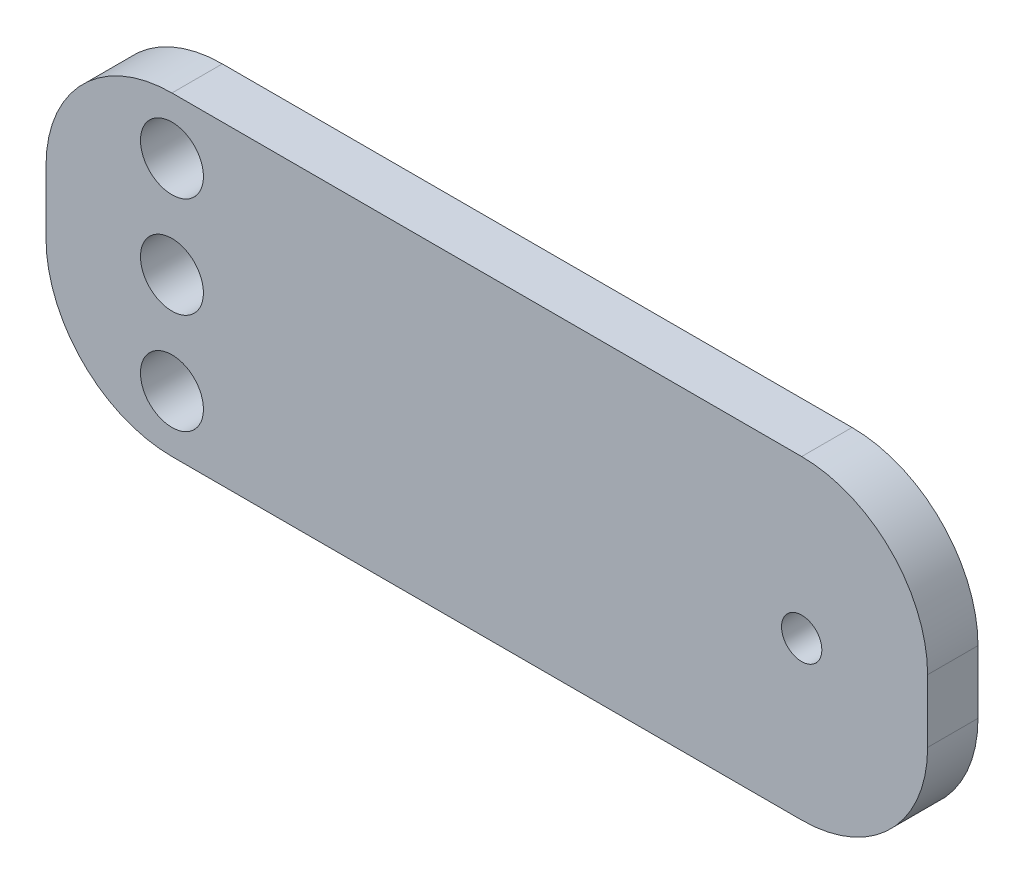
SolidWorks part; units mm, degrees
ref_plane "前视基准面" through (0, 0, 0) normal (0, 0, 1) x (1, 0, 0)
ref_plane "上视基准面" through (0, 0, 0) normal (0, 1, 0) x (1, 0, 0)
ref_plane "右视基准面" through (0, 0, 0) normal (1, 0, 0) x (0, 0, -1)
sketch "草图1" plane through (0, 0, 0) normal (0, 0, 1) x (1, 0, 0)
  line L0 (-35, 0) -> (35, 0) construction
  line L1 (-35, -12.5) -> (35, -12.5)
  line L2 (-35, -12.5) -> (-35, 12.5)
  line L3 (-35, 12.5) -> (35, 12.5)
  line L4 (35, -12.5) -> (35, 12.5)
  line L5 (-35, -12.5) -> (35, 12.5) construction
  line L6 (-35, 12.5) -> (35, -12.5) construction
  line L7 (-25, 0) -> (-25, 16.6595) construction
  line L8 (-25, 16.6595) -> (-25, -14.4543) construction
  circle A0 centre (-25, 0) radius 2.5
  circle A1 centre (25, 0) radius 1.6
  circle A2 centre (-25, 0) radius 8 construction
  circle A3 centre (-25, 8) radius 2.5
  circle A4 centre (-25, -8) radius 2.5
  point P0 (0, 0)
  dimension "D3" = 5
  dimension "D4" = 10
  dimension "D5" = 3.2
  dimension "D6" = 10
  dimension "D7" = 16
  dimension "D1" = 70
  dimension "D2" = 25
extrude "凸台-拉伸1" add sketch "草图1" along normal blind 4
fillet "圆角1" radius 10 4 edges at (-35, 12.5, 2) (-35, -12.5, 2) (35, -12.5, 2) (35, 12.5, 2)
